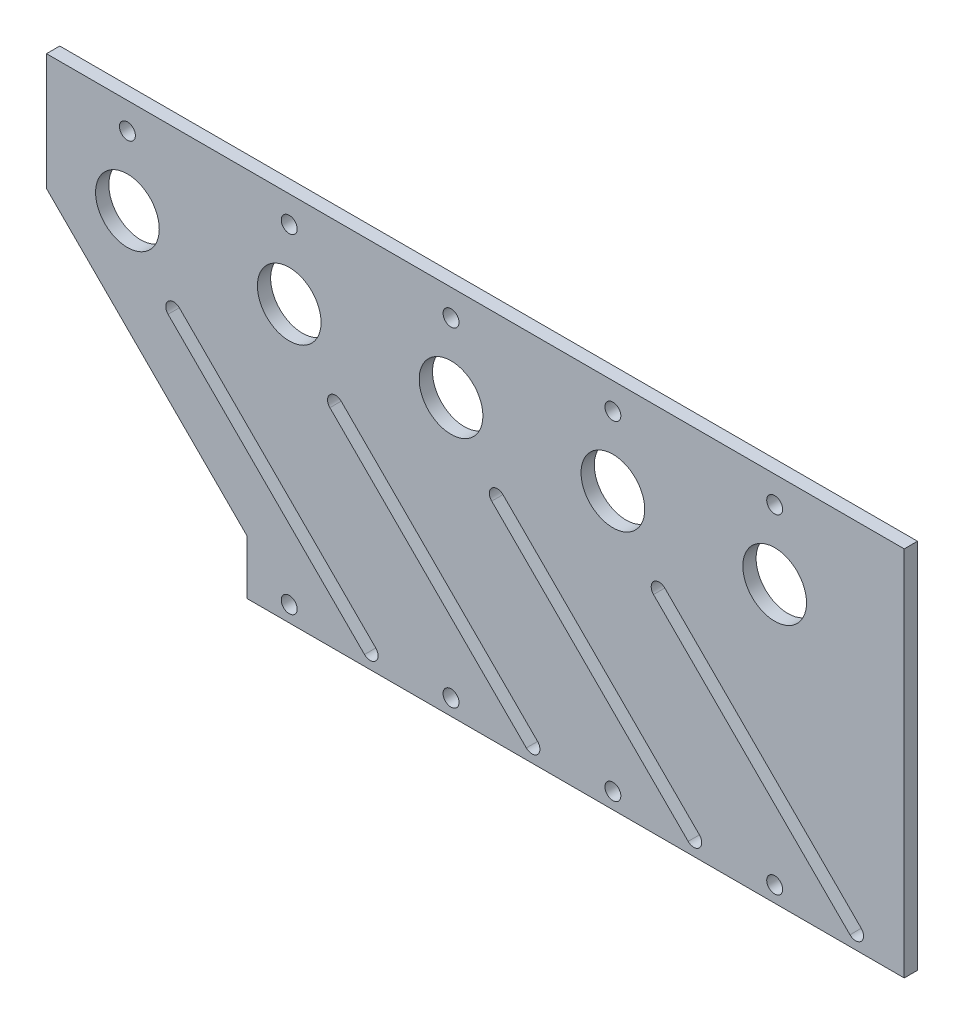
SolidWorks part; units mm, degrees
ref_plane "前视基准面" through (0, 0, 0) normal (0, 0, 1) x (1, 0, 0)
ref_plane "上视基准面" through (0, 0, 0) normal (0, 1, 0) x (1, 0, 0)
ref_plane "右视基准面" through (0, 0, 0) normal (1, 0, 0) x (0, 0, -1)
sketch "草图1" plane through (0, 0, 0) normal (0, 0, 1) x (1, 0, 0)
  line L1 (-150, 35) -> (150, 35)
  line L2 (-150, 35) -> (-150, -35)
  line L3 (-150, -35) -> (150, -35)
  line L4 (150, 35) -> (150, -35)
  line L5 (-150, 35) -> (150, -35) construction
  line L6 (-150, -35) -> (150, 35) construction
  point P0 (0, 0)
  dimension "D1" = 300
  dimension "D2" = 70
extrude "凸台-拉伸1" add sketch "草图1" along normal blind 2.5
sketch "草图2" plane through (0, 0, 2.5) normal (0, 0, 1) x (1, 0, 0)
  line L0 (-150, 35) -> (-150, -35) construction
  line L1 (0, -32) -> (0, 35) construction
  line L2 (150, 35) -> (-150, 35) construction
  line L4 (-103, -32) -> (-140, 5) construction
  line L5 (-104.0607, -33.0607) -> (-141.0607, 3.9393)
  line L6 (-101.9393, -30.9393) -> (-138.9393, 6.0607)
  line L7 (-150, -35) -> (150, -35) construction
  arc A1 (-104.0607, -33.0607) -> (-101.9393, -30.9393) centre (-103, -32) ccw
  arc A2 (-138.9393, 6.0607) -> (-141.0607, 3.9393) centre (-140, 5) ccw
  circle A4 centre (-118.24, -32) radius 1.5
  circle A6 centre (-118.24, 30) radius 1.5
  circle A7 centre (-118.24, 17) radius 6
  point P4 (-121.5, -13.5)
  dimension "D1" = 45
  dimension "D6" = 3
  dimension "D11" = 12
  dimension "D7" = 3
  dimension "D2" = 3
  dimension "D3" = 10
  dimension "D4" = 3
  dimension "D5" = 40
  dimension "D8" = 65
  dimension "D9" = 15.24
  dimension "D12" = 13
extrude "切除-拉伸1" cut sketch "草图2" against normal through all
pattern_linear "阵列(线性)1" count 9 spacing 30.48 along (1, 0, 0) of "切除-拉伸1"
sketch "草图3" plane through (0, 0, 2.5) normal (0, 0, 1) x (1, 0, 0)
  line L0 (-11.56, 35) -> (-11.56, 13)
  line L1 (150, 35) -> (-150, 35) construction
  line L2 (-11.56, 13) -> (26.16, -24.72)
  line L3 (26.16, -24.72) -> (26.16, -35)
  line L4 (-150, -35) -> (150, -35) construction
  line L5 (-26.8, 17) -> (3.68, 17) construction
  line L6 (34.16, -32) -> (26.16, -32) construction
  line L7 (19.9807, -30.9393) -> (-17.0193, 6.0607) construction
  line L11 (-11.56, 35) -> (-150, 35)
  line L12 (-150, 35) -> (-150, -35)
  line L13 (-150, -35) -> (26.16, -35)
  point P12 (-11.56, 17)
  dimension "D1" = 8
  dimension "D2" = 22
extrude "切除-拉伸2" cut sketch "草图3" against normal blind 10
